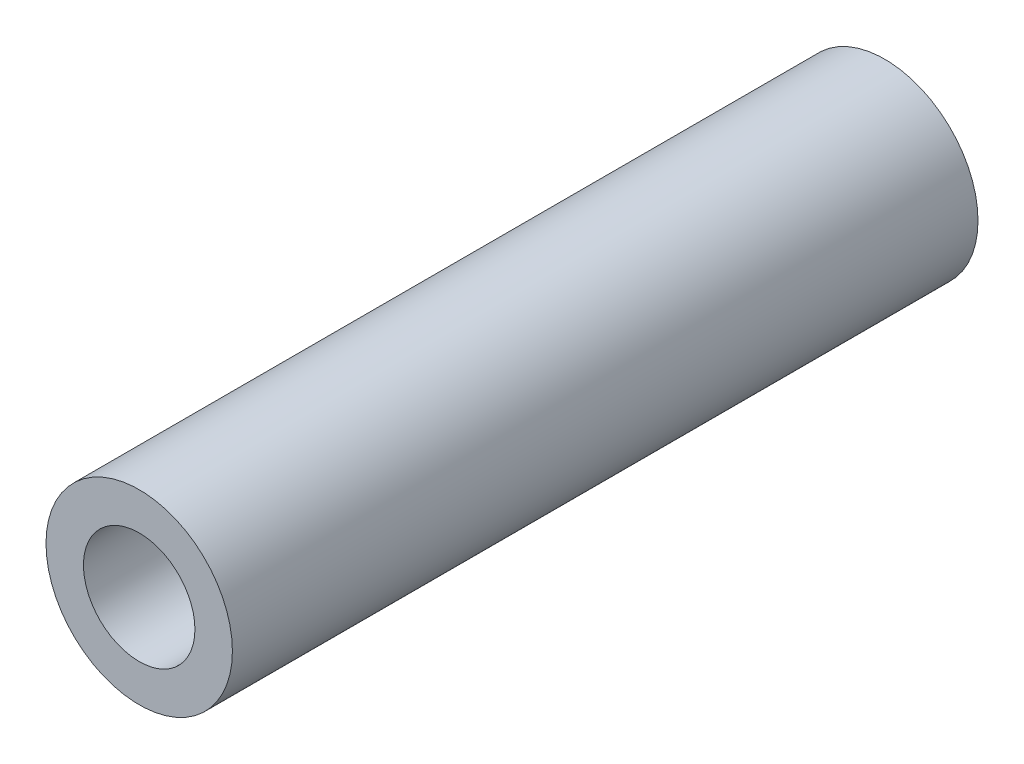
SolidWorks part; units mm, degrees
material "1060 Alloy"
ref_plane "Front Plane" through (0, 0, 0) normal (0, 0, 1) x (1, 0, 0)
ref_plane "Top Plane" through (0, 0, 0) normal (0, 1, 0) x (1, 0, 0)
ref_plane "Right Plane" through (0, 0, 0) normal (1, 0, 0) x (0, 0, -1)
sketch "Sketch1" plane through (0, 0, 0) normal (0, 0, 1) x (1, 0, 0)
  circle A0 centre (0, 0) radius 3.175
  dimension "D1" = 6.35
extrude "Body" add sketch "Sketch1" against normal blind 25.4
hole_wizard "#6 Clearance Hole1" positions "Sketch3" profile "Sketch2" hole size "#6" standard "ANSI Inch" end condition through all
sketch "Sketch3" plane through (0, 0, 0) normal (0, 0, 1) x (1, 0, 0)
  point P0 (0, 0)
sketch "Sketch2" plane through (0, 0, 0) normal (1, 0, 0) x (0, -1, 0)
  line L0 (0, 0) -> (0, 25.4)
  line L1 (0, 25.4) -> (1.8986, 25.4)
  line L2 (1.8986, 25.4) -> (1.8986, 0)
  line L5 (1.8986, 0) -> (0, 0)
  line L11 (0, -6.35) -> (0, 107.95) construction
  dimension "Thru Hole Dia." = 3.7973
  dimension "Thru Hole Depth" = 25.4
